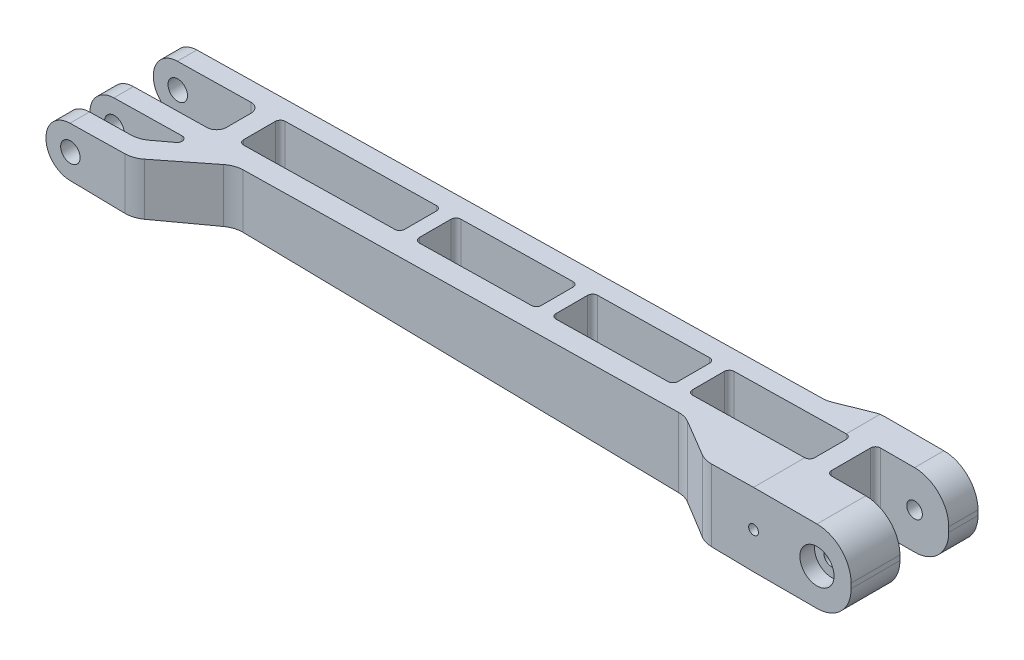
SolidWorks part; units mm, degrees
ref_plane "Front Plane" through (0, 0, 0) normal (0, 0, 1) x (1, 0, 0)
ref_plane "Top Plane" through (0, 0, 0) normal (0, 1, 0) x (1, 0, 0)
ref_plane "Right Plane" through (0, 0, 0) normal (1, 0, 0) x (0, 0, -1)
sketch "Sketch1" plane through (0, 0, 0) normal (0, 1, 0) x (1, 0, 0)
  line L0 (-30.4839, -13.8422) -> (-30.4839, -17.8422)
  line L1 (-30.4839, -0.8422) -> (102.6095, -0.8422)
  line L2 (-30.4839, -0.8422) -> (-30.4839, -4.8422)
  line L3 (-30.4839, -26.8422) -> (-14.3067, -26.8422)
  line L4 (131.5161, -0.8422) -> (131.5161, -3.8422)
  line L5 (-30.4839, -4.8422) -> (-10.4839, -4.8422)
  line L7 (-30.4839, -13.8422) -> (-10.4839, -13.8422)
  line L8 (-8.4839, -6.8422) -> (-8.4839, -11.8422)
  line L9 (-30.4839, -17.8422) -> (-15.4839, -17.8422)
  line L11 (-30.4839, -22.8422) -> (-17.0862, -22.8422)
  line L14 (131.5161, -0.8422) -> (131.5161, 2.1578)
  line L15 (131.5161, 2.1578) -> (112.4228, 2.1578)
  line L19 (131.5161, -23.8422) -> (102.901, -23.8422)
  line L21 (131.5161, -3.8422) -> (117.5161, -3.8422)
  line L23 (131.5161, -13.8422) -> (117.5161, -13.8422)
  line L24 (116.5161, -4.8422) -> (116.5161, -12.8422)
  line L25 (-30.4839, -22.8422) -> (-30.4839, -26.8422)
  line L26 (131.5161, -13.8422) -> (131.5161, -23.8422)
  line L27 (-15.4839, -17.8422) -> (-8.4839, -17.8422) construction
  line L28 (110.6672, 1.8394) -> (104.3651, -0.5238)
  line L30 (0.9347, -17.8422) -> (90.1312, -17.8422)
  line L31 (92.7037, -18.5547) -> (100.3286, -23.1297)
  line L32 (-15.4839, -17.8422) -> (-11.6043, -17.8422)
  line L33 (-0.7453, -17.8422) -> (137.9643, -17.8422) construction
  line L34 (-14.18, -21.9109) -> (-11.0231, -19.6559)
  line L35 (-11.2876, -25.8278) -> (-2.0844, -18.8566)
  line L36 (-3.4839, -4.8422) -> (27.5161, -4.8422)
  line L37 (-4.4839, -5.8422) -> (-4.4839, -12.3362)
  line L38 (-3.4839, -13.3362) -> (27.5161, -13.3362)
  line L39 (28.5161, -5.8422) -> (28.5161, -12.3362)
  line L40 (32.5161, -4.8422) -> (55.5161, -4.8422)
  line L41 (31.5161, -5.8422) -> (31.5161, -12.3362)
  line L42 (32.5161, -13.3362) -> (55.5161, -13.3362)
  line L43 (56.5161, -5.8422) -> (56.5161, -12.3362)
  line L44 (60.5161, -4.8422) -> (83.5161, -4.8422)
  line L45 (59.5161, -5.8422) -> (59.5161, -12.3362)
  line L46 (60.5161, -13.3362) -> (83.5161, -13.3362)
  line L47 (84.5161, -5.8422) -> (84.5161, -12.3362)
  line L48 (88.5161, -4.8422) -> (111.5161, -4.8422)
  line L49 (87.5161, -5.8422) -> (87.5161, -12.3362)
  line L50 (88.5161, -13.3362) -> (111.5161, -13.3362)
  line L51 (112.5161, -5.8422) -> (112.5161, -12.3362)
  arc A0 (-10.4839, -4.8422) -> (-8.4839, -6.8422) centre (-10.4839, -6.8422) cw
  arc A1 (-10.4839, -13.8422) -> (-8.4839, -11.8422) centre (-10.4839, -11.8422) ccw
  arc A2 (104.3651, -0.5238) -> (102.6095, -0.8422) centre (102.6095, 4.1578) cw
  arc A3 (112.4228, 2.1578) -> (110.6672, 1.8394) centre (112.4228, -2.8422) ccw
  arc A4 (117.5161, -3.8422) -> (116.5161, -4.8422) centre (117.5161, -4.8422) ccw
  arc A5 (117.5161, -13.8422) -> (116.5161, -12.8422) centre (117.5161, -12.8422) cw
  arc A6 (-17.0862, -22.8422) -> (-14.18, -21.9109) centre (-17.0862, -17.8422) ccw
  arc A7 (-11.0231, -19.6559) -> (-11.6043, -17.8422) centre (-11.6043, -18.8422) ccw
  arc A8 (-2.0844, -18.8566) -> (0.9347, -17.8422) centre (0.9347, -22.8422) cw
  arc A9 (90.1312, -17.8422) -> (92.7037, -18.5547) centre (90.1312, -22.8422) cw
  arc A10 (-14.3067, -26.8422) -> (-11.2876, -25.8278) centre (-14.3067, -21.8422) ccw
  arc A11 (102.901, -23.8422) -> (100.3286, -23.1297) centre (102.901, -18.8422) cw
  arc A12 (111.5161, -13.3362) -> (112.5161, -12.3362) centre (111.5161, -12.3362) ccw
  arc A13 (111.5161, -4.8422) -> (112.5161, -5.8422) centre (111.5161, -5.8422) cw
  arc A14 (88.5161, -4.8422) -> (87.5161, -5.8422) centre (88.5161, -5.8422) ccw
  arc A15 (87.5161, -12.3362) -> (88.5161, -13.3362) centre (88.5161, -12.3362) ccw
  arc A16 (83.5161, -13.3362) -> (84.5161, -12.3362) centre (83.5161, -12.3362) ccw
  arc A17 (83.5161, -4.8422) -> (84.5161, -5.8422) centre (83.5161, -5.8422) cw
  arc A18 (60.5161, -4.8422) -> (59.5161, -5.8422) centre (60.5161, -5.8422) ccw
  arc A19 (59.5161, -12.3362) -> (60.5161, -13.3362) centre (60.5161, -12.3362) ccw
  arc A20 (55.5161, -13.3362) -> (56.5161, -12.3362) centre (55.5161, -12.3362) ccw
  arc A21 (55.5161, -4.8422) -> (56.5161, -5.8422) centre (55.5161, -5.8422) cw
  arc A22 (32.5161, -4.8422) -> (31.5161, -5.8422) centre (32.5161, -5.8422) ccw
  arc A23 (31.5161, -12.3362) -> (32.5161, -13.3362) centre (32.5161, -12.3362) ccw
  arc A24 (27.5161, -13.3362) -> (28.5161, -12.3362) centre (27.5161, -12.3362) ccw
  arc A25 (-4.4839, -12.3362) -> (-3.4839, -13.3362) centre (-3.4839, -12.3362) ccw
  arc A26 (27.5161, -4.8422) -> (28.5161, -5.8422) centre (27.5161, -5.8422) cw
  arc A27 (-3.4839, -4.8422) -> (-4.4839, -5.8422) centre (-3.4839, -5.8422) ccw
  point P24 (-8.4839, -4.8422)
  point P29 (103.5161, -0.8422)
  point P33 (111.5161, 2.1578)
  point P37 (116.5161, -3.8422)
  point P40 (116.5161, -13.8422)
  point P45 (-15.4839, -22.8422)
  point P53 (91.5161, -17.8422)
  point P59 (101.5161, -23.8422)
  point P79 (112.5161, -4.8422)
  point P82 (87.5161, -4.8422)
  point P89 (84.5161, -4.8422)
  point P92 (59.5161, -4.8422)
  point P99 (56.5161, -4.8422)
  point P102 (31.5161, -4.8422)
  dimension "D15" = 2
  dimension "D16" = 2
  dimension "D18" = 5
  dimension "D19" = 5
  dimension "D21" = 1
  dimension "D22" = 1
  dimension "D23" = 5
  dimension "D24" = 1
  dimension "D12" = 5
  dimension "D25" = 5
  dimension "D26" = 5
  dimension "D35" = 1
  dimension "D1" = 162
  dimension "D2" = 26
  dimension "D3" = 4
  dimension "D4" = 4
  dimension "D5" = 5
  dimension "D6" = 9
  dimension "D7" = 22
  dimension "D8" = 15
  dimension "D9" = 20
  dimension "D10" = 3
  dimension "D11" = 30
  dimension "D13" = 10
  dimension "D14" = 3
  dimension "D17" = 8
  dimension "D20" = 15
  dimension "D27" = 3
  dimension "D28" = 3
  dimension "D29" = 3
  dimension "D30" = 4
  dimension "D31" = 4
  dimension "D32" = 25
  dimension "D33" = 25
  dimension "D34" = 25
  dimension "D36" = 40
extrude "Boss-Extrude1" add sketch "Sketch1" along normal blind 15
sketch "Sketch2" plane through (0, 0, 26.8422) normal (0, 0, 1) x (1, 0, 0)
  line L0 (-30.4839, 12.5) -> (-30.4839, 2.5)
  line L2 (-30.4839, 15) -> (-30.4839, 0) construction
  line L3 (-30.4839, 7.5) -> (111.5161, 7.5) construction
  line L4 (111.5161, 0) -> (111.5161, 15) construction
  line L5 (-30.4839, 12.5) -> (111.5161, 15)
  line L6 (111.5161, 15) -> (111.5161, 0)
  line L7 (111.5161, 0) -> (-30.4839, 2.5)
  line L8 (-30.4839, 12.5) -> (-30.4839, 15)
  line L9 (-30.4839, 15) -> (111.5161, 15)
  line L10 (111.5161, 15) -> (-30.4839, 12.5)
  line L11 (-30.4839, 2.5) -> (-30.4839, 0)
  line L12 (-30.4839, 0) -> (111.5161, 0)
  line L13 (111.5161, 0) -> (-30.4839, 2.5)
  line M7 (-30.4839, 0) -> (-14.3067, 0)
  line M8 (-14.3067, 0) -> (-14.3067, 15)
  line M9 (-14.3067, 15) -> (-30.4839, 15)
  line M10 (-30.4839, 15) -> (-30.4839, 0)
  dimension "D1" = 5
  dimension "D2" = 142
  dimension "D3" = 7.5
extrude "Cut-Extrude1" cut sketch "Sketch2" against normal through all contours L7 M8 M10 M7 | L12 L7 M8 | L5 M10 M8 M9 | L9 L5 M8
sketch "Sketch3" plane through (0, 0, 26.8422) normal (0, 0, 1) x (1, 0, 0)
  line L0 (-30.4839, 7.5) -> (-14.3067, 7.5) construction
  line L1 (-30.4839, 12.5) -> (-30.4839, 2.5) construction
  line L2 (-14.3067, 12.7848) -> (-14.3067, 2.2152) construction
  circle A0 centre (-25.4839, 7.5) radius 2
  dimension "D1" = 4
  dimension "D2" = 5
extrude "Cut-Extrude2" cut sketch "Sketch3" against normal through all
sketch "Sketch4" plane through (0, 0, 23.8422) normal (0, 0, 1) x (1, 0, 0)
  line L0 (131.5161, 7.5) -> (102.901, 7.5) construction
  line L1 (131.5161, 15) -> (131.5161, 0) construction
  line L2 (102.901, 14.8483) -> (102.901, 0.1517) construction
  circle A0 centre (124.5161, 7.5) radius 1.6
  dimension "D1" = 3.2
  dimension "D2" = 7
sketch "Sketch5" plane through (0, 0, 26.8422) normal (0, 0, 1) x (1, 0, 0)
  line L0 (-30.4839, 7.5) -> (-14.3067, 7.5) construction
  line L1 (-30.4839, 12.5) -> (-30.4839, 2.5) construction
  line L2 (-14.3067, 12.7848) -> (-14.3067, 2.2152) construction
  line L3 (-25.4839, 9.5) -> (-25.4839, 5.5) construction
  circle A0 centre (-25.4839, 7.5) radius 2 construction
extrude "Cut-Extrude3" cut sketch "Sketch4" against normal through all
fillet "Fillet1" radius 5 6 edges at (-30.4839, 12.5, 24.8422) (-30.4839, 12.5, 15.8422) (-30.4839, 12.5, 2.8422) (-30.4839, 2.5, 2.8422) (-30.4839, 2.5, 15.8422) (-30.4839, 2.5, 24.8422)
fillet "Fillet2" radius 7 4 edges at (131.5161, 15, 18.8422) (131.5161, 15, 0.8422) (131.5161, 0, 0.8422) (131.5161, 0, 18.8422)
sketch "Sketch6" plane through (0, 0, 23.8422) normal (0, 0, 1) x (1, 0, 0)
  circle A0 centre (124.5161, 7.5) radius 3.5
  dimension "D1" = 7
extrude "Cut-Extrude4" cut sketch "Sketch6" against normal blind 3
sketch "Sketch7" plane through (0, 0, 23.8422) normal (0, 0, 1) x (1, 0, 0)
  line L0 (124.5161, 7.5) -> (106.842, 7.5) construction
  circle A0 centre (111.5161, 7.5) radius 1
  dimension "D1" = 2
  dimension "D2" = 13
extrude "Cut-Extrude5" cut sketch "Sketch7" against normal blind 5
